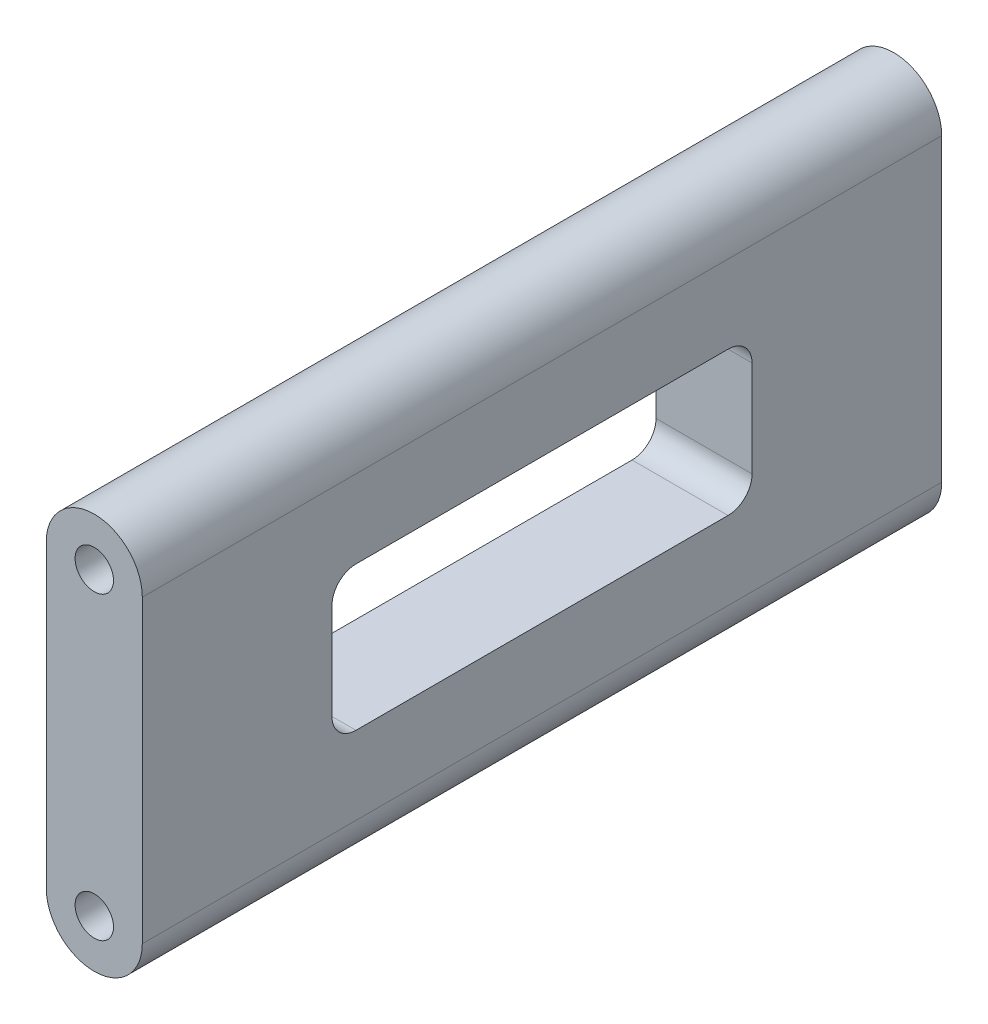
SolidWorks part; units mm, degrees
material "ABS"
ref_plane "前视基准面" through (0, 0, 0) normal (0, 0, 1) x (1, 0, 0)
ref_plane "上视基准面" through (0, 0, 0) normal (0, 1, 0) x (1, 0, 0)
ref_plane "右视基准面" through (0, 0, 0) normal (1, 0, 0) x (0, 0, -1)
sketch "草图1" plane through (0, 0, 0) normal (0, 0, 1) x (1, 0, 0)
  line L0 (0, -12.5) -> (0, 12.5) construction
  line L1 (-4, -12.5) -> (-4, 12.5)
  line L2 (4, -12.5) -> (4, 12.5)
  arc A0 (-4, -12.5) -> (4, -12.5) centre (0, -12.5) ccw
  arc A1 (4, 12.5) -> (-4, 12.5) centre (0, 12.5) ccw
  circle A2 centre (0, 12.5) radius 1.6
  circle A3 centre (0, -12.5) radius 1.6
  point P2 (0, 0)
  dimension "D1" = 3.2
  dimension "D2" = 3.2
  dimension "D3" = 8
  dimension "D4" = 25
extrude "凸台-拉伸1" add sketch "草图1" along normal blind 66.6
sketch "草图2" plane through (4, 0, 0) normal (1, 0, 0) x (0, 0, -1)
  line L0 (0, 0) -> (-66.6, 0) construction
  line L1 (-66.6, -12.5) -> (-66.6, 12.5) construction
  line L3 (-17.8, -6) -> (-48.8, -6)
  line L4 (-15.8, -4) -> (-15.8, 4)
  line L5 (-17.8, 6) -> (-48.8, 6)
  line L6 (-50.8, -4) -> (-50.8, 4)
  line L7 (-15.8, -6) -> (-50.8, 6) construction
  line L8 (-15.8, 6) -> (-50.8, -6) construction
  arc A0 (-48.8, -6) -> (-50.8, -4) centre (-48.8, -4) cw
  arc A1 (-17.8, -6) -> (-15.8, -4) centre (-17.8, -4) ccw
  arc A2 (-15.8, 4) -> (-17.8, 6) centre (-17.8, 4) ccw
  arc A3 (-48.8, 6) -> (-50.8, 4) centre (-48.8, 4) ccw
  point P5 (-33.3, 0)
  dimension "D3" = 2
  dimension "D1" = 35
  dimension "D2" = 12
extrude "切除-拉伸1" cut sketch "草图2" against normal through all
